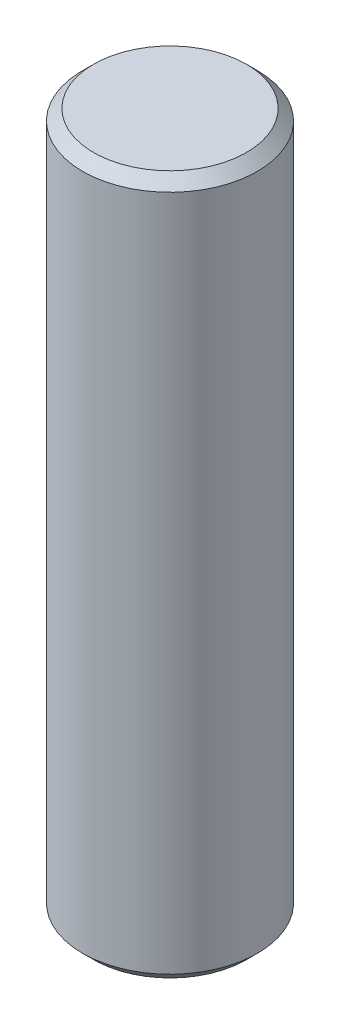
SolidWorks part; units mm, degrees
material "Plain Carbon Steel"
ref_plane "Front Plane" through (0, 0, 0) normal (1, 0, 0) x (0, 1, 0)
ref_plane "Top Plane" through (0, 0, 0) normal (0, 0, 1) x (0, 1, 0)
ref_plane "Right Plane" through (0, 0, 0) normal (0, 1, 0) x (-1, 0, 0)
sketch "Sketch1" plane through (0, 0, 0) normal (1, 0, 0) x (0, 1, 0)
  line L0 (-12.7, 0) -> (12.7, 0)
  line L1 (-12.7, 0) -> (-12.7, 2.7788)
  line L2 (-12.7, 2.7788) -> (-12.3038, 3.175)
  line L3 (-12.3038, 3.175) -> (12.3038, 3.175)
  line L4 (12.3038, 3.175) -> (12.7, 2.7788)
  line L5 (12.7, 2.7788) -> (12.7, 0)
  point P4 (0, 0)
  dimension "D1" = 25.4
  dimension "D2" = 3.175
  dimension "D3" = 45
  dimension "D4" = 0.3962
revolve "Revolve1" add sketch "Sketch1" angle 360 about L0
